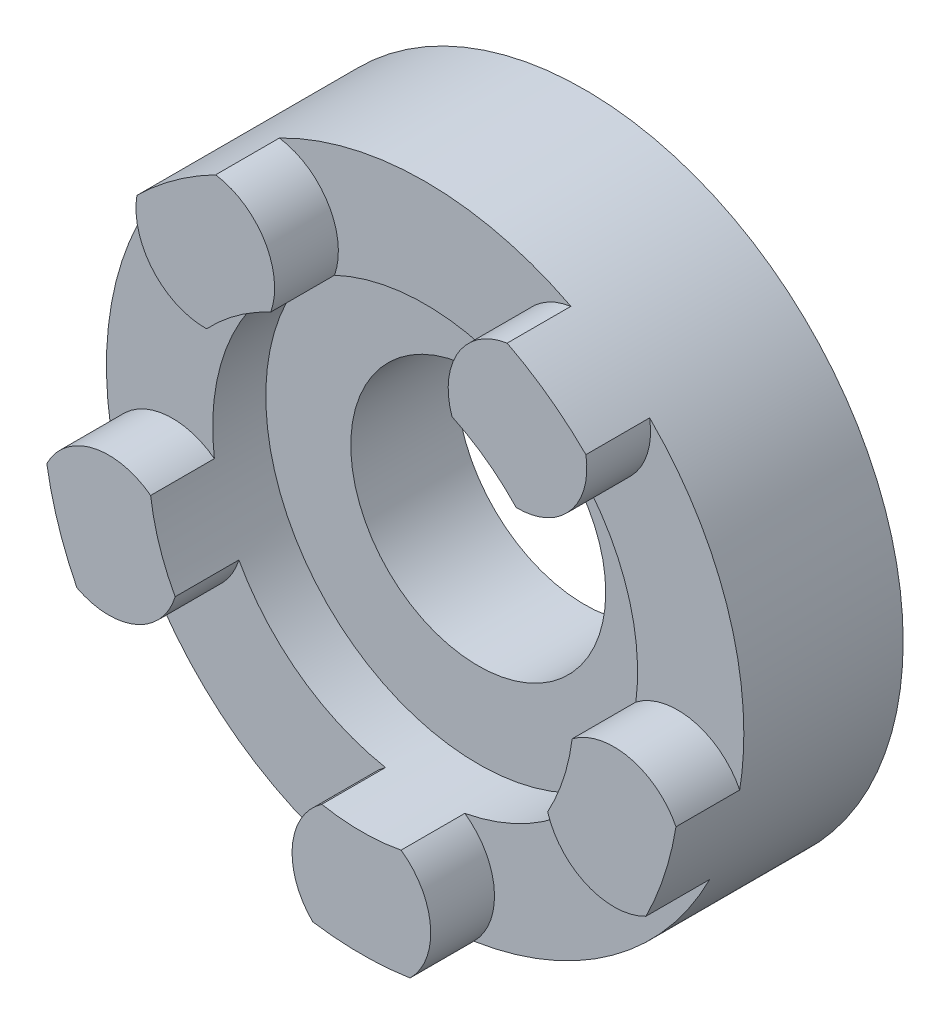
SolidWorks part; units mm, degrees
ref_plane "Front Plane" through (0, 0, 0) normal (0, 0, 1) x (1, 0, 0)
ref_plane "Top Plane" through (0, 0, 0) normal (0, 1, 0) x (1, 0, 0)
ref_plane "Right Plane" through (0, 0, 0) normal (1, 0, 0) x (0, 0, -1)
sketch "Sketch1" plane through (0, 0, 0) normal (0, 0, 1) x (1, 0, 0)
  circle A0 centre (0, 0) radius 10
  circle A1 centre (0, 0) radius 15
  circle A2 centre (0, 0) radius 6
extrude "Boss-Extrude1" add sketch "Sketch1" against normal blind 5 contours A1 A0 | A0 A2
sketch "Sketch2" plane through (0, 0, 0) normal (0, 0, 1) x (1, 0, 0)
  circle A0 centre (0, 0) radius 10
  circle A1 centre (0, 0) radius 15
extrude "Boss-Extrude2" add sketch "Sketch2" along normal blind 2.5
sketch "Sketch3" plane through (0, 0, 2.5) normal (0, 0, 1) x (1, 0, 0)
  line L0 (0, 0) -> (0, -15) construction
  circle A0 centre (0, 0) radius 15 construction
  arc A1 (-2.2906, -14.8241) -> (2.2906, -14.8241) centre (0, 0) ccw
  arc A2 (-1.8675, -9.8241) -> (1.8675, -9.8241) centre (0, 0) ccw
  arc A5 (3.2352, -12.0741) -> (2.2906, -14.8241) centre (0, -12.5) cw
  arc A6 (3.2352, -12.0741) -> (1.8675, -9.8241) centre (0, -12.5) ccw
  arc A7 (-3.2352, -12.0741) -> (-2.2906, -14.8241) centre (0, -12.5) ccw
  arc A8 (-3.2352, -12.0741) -> (-1.8675, -9.8241) centre (0, -12.5) cw
  arc A37 (-14.8064, -2.4024) -> (-13.3907, -6.7594) centre (0, 0) ccw
  arc A38 (-9.9203, -1.2597) -> (-8.7662, -4.8119) centre (0, 0) ccw
  arc A39 (-10.4834, -6.808) -> (-13.3907, -6.7594) centre (-11.8882, -3.8627) cw
  arc A40 (-10.4834, -6.808) -> (-8.7662, -4.8119) centre (-11.8882, -3.8627) ccw
  arc A41 (-12.4829, -0.6542) -> (-14.8064, -2.4024) centre (-11.8882, -3.8627) ccw
  arc A42 (-12.4829, -0.6542) -> (-9.9203, -1.2597) centre (-11.8882, -3.8627) cw
  arc A43 (-6.8602, 13.3393) -> (-10.5665, 10.6465) centre (0, 0) ccw
  arc A44 (-4.2636, 9.0455) -> (-7.2853, 6.8501) centre (0, 0) ccw
  arc A45 (-9.7143, 7.8665) -> (-10.5665, 10.6465) centre (-7.3473, 10.1127) cw
  arc A46 (-9.7143, 7.8665) -> (-7.2853, 6.8501) centre (-7.3473, 10.1127) ccw
  arc A47 (-4.4796, 11.6698) -> (-6.8602, 13.3393) centre (-7.3473, 10.1127) ccw
  arc A48 (-4.4796, 11.6698) -> (-4.2636, 9.0455) centre (-7.3473, 10.1127) cw
  arc A49 (10.5665, 10.6465) -> (6.8602, 13.3393) centre (0, 0) ccw
  arc A50 (7.2853, 6.8501) -> (4.2636, 9.0455) centre (0, 0) ccw
  arc A51 (4.4796, 11.6698) -> (6.8602, 13.3393) centre (7.3473, 10.1127) cw
  arc A52 (4.4796, 11.6698) -> (4.2636, 9.0455) centre (7.3473, 10.1127) ccw
  arc A53 (9.7143, 7.8665) -> (10.5665, 10.6465) centre (7.3473, 10.1127) ccw
  arc A54 (9.7143, 7.8665) -> (7.2853, 6.8501) centre (7.3473, 10.1127) cw
  arc A55 (13.3907, -6.7594) -> (14.8064, -2.4024) centre (0, 0) ccw
  arc A56 (8.7662, -4.8119) -> (9.9203, -1.2597) centre (0, 0) ccw
  arc A57 (12.4829, -0.6542) -> (14.8064, -2.4024) centre (11.8882, -3.8627) cw
  arc A58 (12.4829, -0.6542) -> (9.9203, -1.2597) centre (11.8882, -3.8627) ccw
  arc A59 (10.4834, -6.808) -> (13.3907, -6.7594) centre (11.8882, -3.8627) ccw
  arc A60 (10.4834, -6.808) -> (8.7662, -4.8119) centre (11.8882, -3.8627) cw
  point P12 (3.2352, -12.0741)
  point P15 (-3.2352, -12.0741)
  point P21 (-10.4834, -6.808)
  point P24 (-12.4829, -0.6542)
  point P31 (-9.7143, 7.8665)
  point P33 (-4.4796, 11.6698)
  point P40 (4.4796, 11.6698)
  point P42 (9.7143, 7.8665)
  point P49 (12.4829, -0.6542)
  point P51 (10.4834, -6.808)
  dimension "D1" = 5
extrude "Boss-Extrude4" add sketch "Sketch3" along normal blind 3
